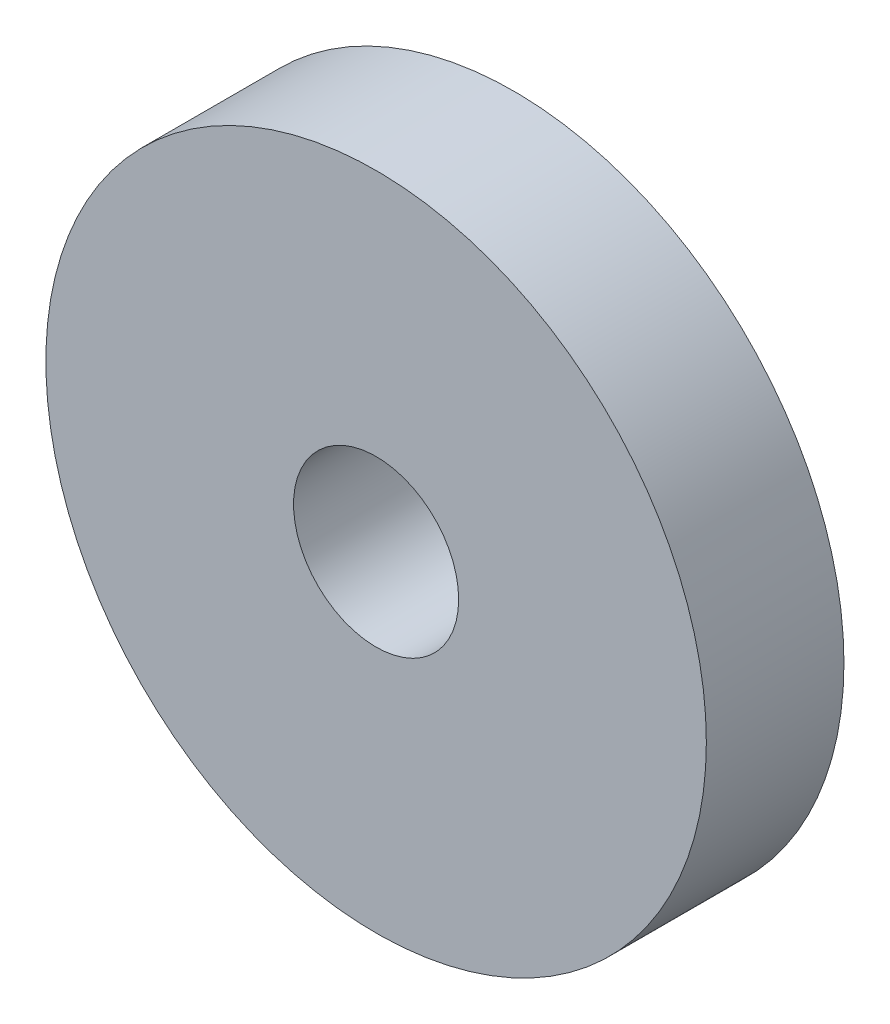
SolidWorks part; units mm, degrees
ref_plane "前视基准面" through (0, 0, 0) normal (0, 0, 1) x (1, 0, 0)
ref_plane "上视基准面" through (0, 0, 0) normal (0, 1, 0) x (1, 0, 0)
ref_plane "右视基准面" through (0, 0, 0) normal (1, 0, 0) x (0, 0, -1)
sketch "草图1" plane through (0, 0, 0) normal (0, 0, 1) x (1, 0, 0)
  circle A0 centre (0, 0) radius 3
  circle A1 centre (0, 0) radius 12
extrude "凸台-拉伸1" add sketch "草图1" along normal blind 5
